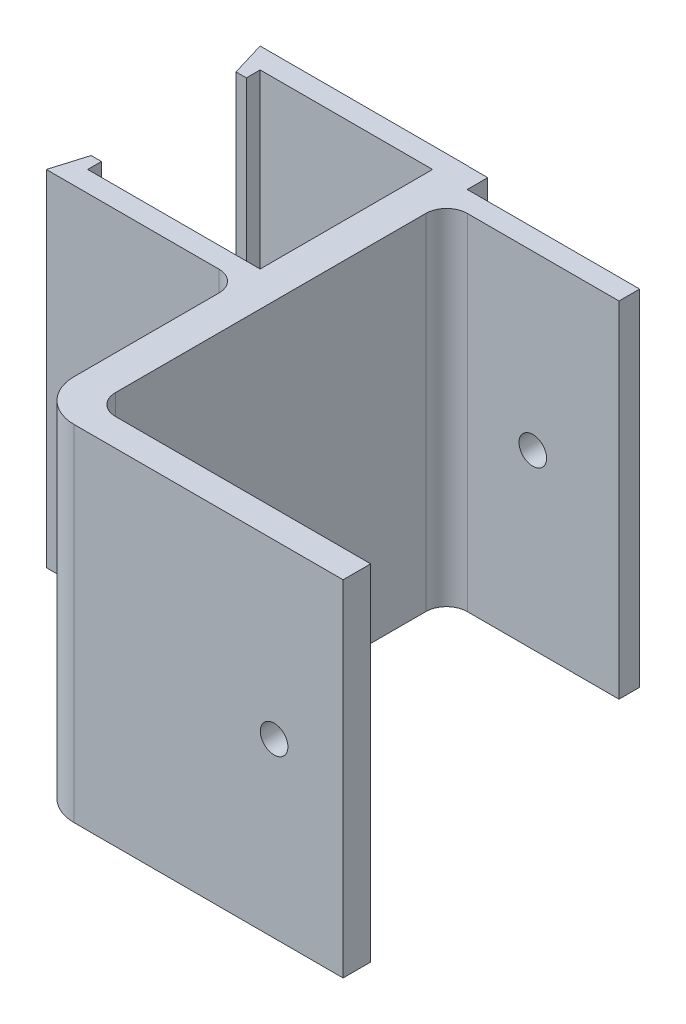
SolidWorks part; units mm, degrees
ref_plane "Спереди" through (0, 0, 0) normal (0, 0, 1) x (1, 0, 0)
ref_plane "Сверху" through (0, 0, 0) normal (0, 1, 0) x (1, 0, 0)
ref_plane "Справа" through (0, 0, 0) normal (1, 0, 0) x (0, 0, -1)
sketch "Эскиз1" plane through (0, 0, 0) normal (0, 1, 0) x (1, 0, 0)
  line L0 (-66.8258, 34.9697) -> (-66.8258, 29.9697)
  line L1 (-63.8258, 29.9697) -> (-63.8258, 31.9697)
  line L2 (-63.8258, 31.9697) -> (-38.8258, 31.9697)
  line L3 (-38.8258, 31.9697) -> (-38.8258, 6.9697)
  line L4 (-38.8258, 6.9697) -> (-63.8258, 6.9697)
  line L5 (-63.8258, 6.9697) -> (-63.8258, 8.9697)
  line L6 (-63.8258, 8.9697) -> (-66.8258, 8.9697)
  line L7 (-66.8258, 8.9697) -> (-66.8258, 3.9697)
  line L8 (-66.8258, 3.9697) -> (-22.1235, 3.9697)
  line L9 (-22.1235, 3.9697) -> (-36.579, 34.9697)
  line L10 (-36.579, 34.9697) -> (-66.8258, 34.9697)
  line L11 (-66.8258, 29.9697) -> (-63.8258, 29.9697)
  point P13 (0, 0)
  point P14 (-63.7308, 29.7758)
  dimension "D1" = 25
  dimension "D2" = 25
  dimension "D3" = 25
  dimension "D4" = 155
  dimension "D5" = 3
  dimension "D6" = 3
  dimension "D7" = 3
  dimension "D8" = 3
  dimension "D9" = 2
  dimension "D10" = 2
extrude "Бобышка-Вытянуть1" add sketch "Эскиз1" along normal blind 110
sketch "Эскиз3" plane through (0, 0, 0) normal (0, -1, 0) x (1, 0, 0)
  line L0 (-66.8258, -3.9697) -> (-65.3258, -8.9697)
  line L1 (-63.8258, -8.9697) -> (-66.8258, -8.9697) construction
  line L2 (-65.3258, -8.9697) -> (-66.8258, -8.9697)
  line L3 (-66.8258, -8.9697) -> (-66.8258, -3.9697)
  line L4 (-66.8258, -29.9697) -> (-66.8258, -34.9697)
  line L5 (-66.8258, -34.9697) -> (-65.3258, -29.9697)
  line L6 (-66.8258, -29.9697) -> (-63.8258, -29.9697) construction
  line L7 (-65.3258, -29.9697) -> (-66.8258, -29.9697)
extrude "Вырез-Вытянуть4" cut sketch "Эскиз3" against normal through all
sketch "Эскиз7" plane through (0, 0, 0) normal (0, -1, 0) x (-1, 0, 0)
  line L1 (36.0076, 1.3029) -> (19.3993, 1.3029)
  line L2 (36.0076, 1.3029) -> (36.0076, 39.7765)
  line L3 (36.0076, 39.7765) -> (19.3993, 39.7765)
  line L4 (19.3993, 1.3029) -> (19.3993, 39.7765)
extrude "Вырез-Вытянуть14" cut sketch "Эскиз7" against normal through all
sketch "Эскиз8" plane through (0, 0, 0) normal (0, -1, 0) x (-1, 0, 0)
  line L0 (66.8258, 3.9697) -> (36.0076, 3.9697) construction
  line L1 (38.7989, 3.9697) -> (33.7989, 3.9697)
  line L2 (38.7989, 3.9697) -> (38.7989, 34.9383)
  line L3 (38.7989, 34.9383) -> (33.7989, 34.9383)
  line L4 (33.7989, 3.9697) -> (33.7989, 34.9383)
  dimension "D1" = 5
extrude "Бобышка-Вытянуть2" add sketch "Эскиз8" against normal up to surface (110 mm away) up to face at (-54.2963, 110, -20.5678)
sketch "Эскиз10" plane through (0, 0, 0) normal (0, -1, 0) x (1, 0, 0)
  line L0 (-38.8258, -6.9697) -> (-63.8258, -6.9697) construction
  line L1 (-33.7989, -3.9697) -> (-38.7989, -3.9697)
  line L2 (-33.7989, -3.9697) -> (-33.7989, 22.0303)
  line L3 (-33.7989, 22.0303) -> (-38.7989, 22.0303)
  line L4 (-38.7989, -3.9697) -> (-38.7989, 22.0303)
  dimension "D1" = 5
  dimension "D2" = 29
extrude "Бобышка-Вытянуть4" add sketch "Эскиз10" against normal up to surface (110 mm away) up to face at (-52.7142, 110, -21.6795)
sketch "Эскиз16" plane through (0, 110, 0) normal (0, 1, 0) x (1, 0, 0)
  line L0 (-33.7989, 34.9383) -> (-33.7989, -22.0303) construction
  line L1 (-38.7989, -22.0303) -> (6.2011, -22.0303)
  line L2 (-38.7989, -22.0303) -> (-38.7989, -26.0303)
  line L3 (-38.7989, -26.0303) -> (6.2011, -26.0303)
  line L4 (6.2011, -22.0303) -> (6.2011, -26.0303)
  point P7 (6.2011, -24.0303)
  dimension "D1" = 40
  dimension "D2" = 4
extrude "Бобышка-Вытянуть7" add sketch "Эскиз16" against normal through all
fillet "Скругление4" radius 3 2 edges at (-38.7989, 55, -3.9697) (-33.7989, 55, 22.0303)
fillet "Скругление5" radius 6 1 edges at (-38.7989, 55, 26.0303)
sketch "Эскиз18" plane through (6.2011, 0, 0) normal (1, 0, 0) x (0, 0, -1)
  line L0 (34.9383, 110) -> (-19.0303, 110) construction
  line L1 (-53.1264, 60) -> (60.5458, 60)
  line L2 (-53.1264, 60) -> (-53.1264, -1.6498)
  line L3 (-53.1264, -1.6498) -> (60.5458, -1.6498)
  line L4 (60.5458, 60) -> (60.5458, -1.6498)
  dimension "D1" = 50
extrude "Вырез-Вытянуть18" cut sketch "Эскиз18" against normal through all
sketch "Эскиз19" plane through (0, 0, -34.9697) normal (0, 0, -1) x (-1, 0, 0)
  line L0 (66.8258, 85) -> (-6.2011, 85) construction
  line L1 (66.8258, 110) -> (66.8258, 60) construction
  line L2 (-6.2011, 60) -> (-6.2011, 110) construction
  line L3 (51.7024, 110) -> (51.7024, 60) construction
  line L4 (36.579, 110) -> (66.8258, 110) construction
  line L5 (36.579, 60) -> (66.8258, 60) construction
  line L6 (3.7989, 110) -> (3.7989, 60) construction
  line L7 (-6.2011, 110) -> (30.7989, 110) construction
  line L8 (30.7989, 60) -> (-6.2011, 60) construction
  circle A0 centre (51.7024, 85) radius 2.1
  circle A1 centre (3.7989, 85) radius 2
  dimension "D1" = 10
extrude "Вырез-Вытянуть19" cut sketch "Эскиз19" against normal through all
sketch "Эскиз22" plane through (0, 60, 0) normal (0, -1, 0) x (1, 0, 0)
  line L0 (-33.7989, -34.9383) -> (-33.7989, 19.0303) construction
  line L1 (-33.7989, -28.9697) -> (-8.7989, -28.9697)
  line L2 (-33.7989, -28.9697) -> (-33.7989, -31.9697)
  line L3 (-33.7989, -31.9697) -> (-8.7989, -31.9697)
  line L4 (-8.7989, -28.9697) -> (-8.7989, -31.9697)
  dimension "D1" = 3
  dimension "D2" = 3
  dimension "D3" = 25
extrude "Бобышка-Вытянуть10" add sketch "Эскиз22" against normal up to surface (50 mm away) up to face at (-43.3254, 110, -8.0028)
fillet "Скругление7" radius 3 1 edges at (-33.7989, 85, -28.9697)
sketch "Эскиз23" plane through (0, 0, -31.9697) normal (0, 0, -1) x (-1, 0, 0)
  line L0 (8.7989, 85) -> (33.7989, 85) construction
  line L1 (8.7989, 110) -> (8.7989, 60) construction
  line L2 (33.7989, 110) -> (33.7989, 60) construction
  circle A0 centre (21.2989, 85) radius 2
extrude "Вырез-Вытянуть24" cut sketch "Эскиз23" against normal blind 10
